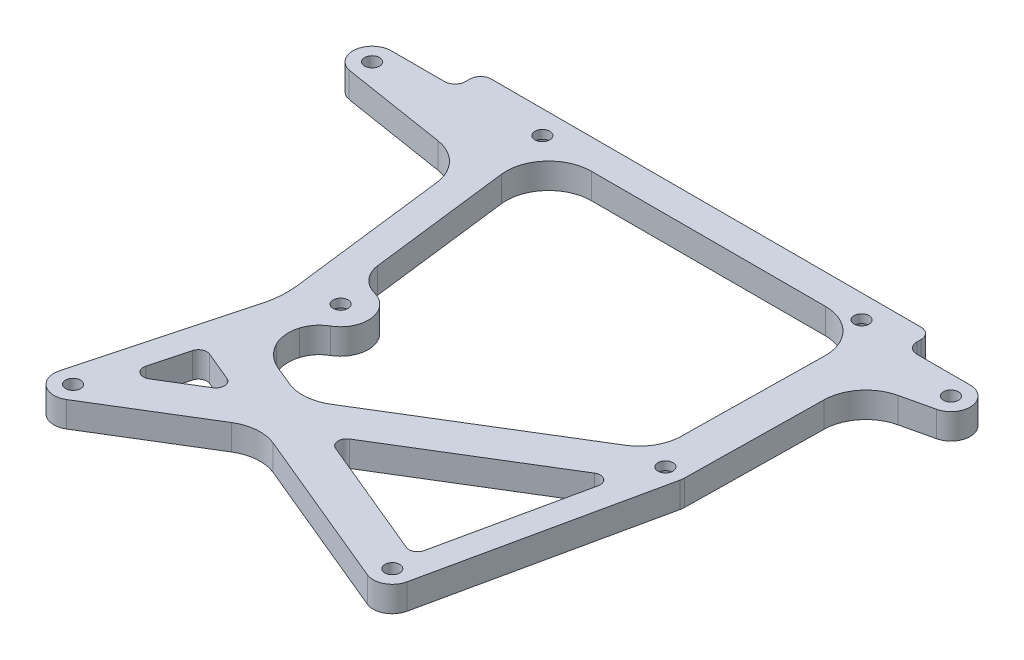
SolidWorks part; units mm, degrees
material "ABS"
ref_plane "Спереди" through (0, 0, 0) normal (0, 0, 1) x (1, 0, 0)
ref_plane "Сверху" through (0, 0, 0) normal (0, 1, 0) x (1, 0, 0)
ref_plane "Справа" through (0, 0, 0) normal (1, 0, 0) x (0, 0, -1)
sketch "Эскиз1" plane through (0, 0, 0) normal (0, 1, 0) x (1, 0, 0)
  line L0 (0, 100.75) -> (0, 0) construction
  line L1 (0, 0) -> (136, 0) construction
  line L2 (136, 0) -> (136, 100.75) construction
  line L3 (136, 100.75) -> (0, 100.75) construction
  line L4 (110, 105.75) -> (110, 52.79) construction
  line L5 (116.88, 52.79) -> (45.62, 52.79) construction
  line L6 (35, 105.75) -> (110, 105.75) construction
  line L7 (45.62, 47.74) -> (45.62, 52.79) construction
  line L9 (110, 105.75) -> (136, 100.75) construction
  line L10 (68, 100.75) -> (68, 0) construction
  line L11 (0, 105.25) -> (12.5, 105.25)
  line L12 (-1.0066, 96.364) -> (23.7971, 92.4355)
  line L13 (48, 104.25) -> (103, 104.25)
  line L14 (26.1533, 1.1647) -> (36.2211, 38.738)
  line L15 (112.8201, 41.0748) -> (105.5618, 7.4046)
  line L16 (47.628, 15.7413) -> (38.3168, 10.051)
  line L17 (121.2789, 51.8417) -> (109.8989, -0.9483)
  line L18 (32.1582, 83.7773) -> (36.7535, 46.3518)
  line L19 (15, 107.75) -> (15, 108.75)
  line L20 (112.9989, 94.1001) -> (112.5003, 60.8462)
  line L21 (121.8644, 85.0635) -> (121.3795, 52.7225)
  line L22 (51.2328, 27.4284) -> (55.7645, 25.5449)
  line L23 (40.3465, 22.2067) -> (47.3526, 19.2947)
  line L24 (107.7161, 52.4634) -> (64.8172, 26.2463)
  line L25 (109.8221, 43.2028) -> (74.0915, 21.3666)
  line L26 (35.342, 12.2751) -> (37.647, 20.8775)
  line L27 (74.3668, 17.8132) -> (102.8391, 5.9792)
  line L28 (65.9549, 11.563) -> (103.7729, -4.1554)
  line L29 (56.9023, 10.8616) -> (32.8466, -3.8397)
  line L30 (129.6138, 94.6573) -> (137.0123, 96.3653)
  line L31 (38.0745, 93.0313) -> (42.1383, 59.9344)
  line L32 (17.5, 111.25) -> (118.5, 111.25)
  line L33 (121, 108.75) -> (121, 107.75)
  line L34 (123.5, 105.25) -> (136, 105.25)
  circle A0 centre (35, 105.75) radius 1.75
  circle A1 centre (110, 105.75) radius 1.75
  circle A2 centre (116.88, 52.79) radius 1.75
  circle A3 centre (45.62, 47.74) radius 1.75
  circle A4 centre (0, 100.75) radius 1.75
  circle A5 centre (136, 100.75) radius 1.75
  circle A6 centre (30.5, 0) radius 1.75
  circle A7 centre (105.5, 0) radius 1.75
  arc A8 (121, 107.75) -> (123.5, 105.25) centre (123.5, 107.75) ccw
  arc A9 (118.5, 111.25) -> (121, 108.75) centre (118.5, 108.75) cw
  arc A10 (0, 105.25) -> (-1.0066, 96.364) centre (0, 100.75) ccw
  arc A11 (137.0123, 96.3653) -> (136, 105.25) centre (136, 100.75) ccw
  arc A12 (112.9989, 94.1001) -> (103, 104.25) centre (103, 94.25) ccw
  arc A13 (38.0745, 93.0313) -> (48, 104.25) centre (48, 94.25) cw
  arc A14 (15, 108.75) -> (17.5, 111.25) centre (17.5, 108.75) cw
  arc A15 (121.2789, 51.8417) -> (121.3795, 52.7225) centre (116.88, 52.79) ccw
  arc A16 (26.1533, 1.1647) -> (32.8466, -3.8397) centre (30.5, 0) ccw
  arc A17 (103.7729, -4.1554) -> (109.8989, -0.9483) centre (105.5, 0) ccw
  arc A18 (121.8644, 85.0635) -> (129.6138, 94.6573) centre (131.8633, 84.9136) cw
  arc A19 (32.1582, 83.7773) -> (23.7971, 92.4355) centre (22.2328, 82.5586) ccw
  arc A20 (65.9549, 11.563) -> (56.9023, 10.8616) centre (62.1169, 2.3289) ccw
  arc A21 (107.7161, 52.4634) -> (112.5003, 60.8462) centre (102.5014, 60.9961) ccw
  arc A22 (51.2328, 27.4284) -> (46.2025, 32.0417) centre (55.0708, 36.6626) cw
  arc A23 (64.8172, 26.2463) -> (55.7645, 25.5449) centre (59.6025, 34.779) cw
  arc A24 (36.7535, 46.3518) -> (36.2211, 38.738) centre (16.9026, 43.9144) cw
  arc A25 (105.5618, 7.4046) -> (102.8391, 5.9792) centre (103.6067, 7.826) cw
  arc A26 (112.8201, 41.0748) -> (109.8221, 43.2028) centre (110.865, 41.4963) ccw
  arc A27 (74.0915, 21.3666) -> (74.3668, 17.8132) centre (75.1344, 19.66) ccw
  arc A28 (47.3526, 19.2947) -> (47.628, 15.7413) centre (46.585, 17.4479) cw
  arc A29 (35.342, 12.2751) -> (38.3168, 10.051) centre (37.2739, 11.7575) ccw
  arc A30 (40.3465, 22.2067) -> (37.647, 20.8775) centre (39.5789, 20.3599) ccw
  arc A31 (15, 107.75) -> (12.5, 105.25) centre (12.5, 107.75) cw
  arc A32 (48.8562, 42.1029) -> (47.2889, 54.0221) centre (45.62, 47.74) ccw
  arc A33 (45.6501, 38.0883) -> (48.8562, 42.1029) centre (52.3413, 36.0321) cw
  arc A34 (42.1383, 59.9344) -> (47.2889, 54.0221) centre (49.0862, 60.7874) ccw
  arc A35 (46.2025, 32.0417) -> (45.6501, 38.0883) centre (53.2972, 35.7384) cw
  point P28 (121, 105.25)
  point P98 (111.1575, 54.79)
  dimension "D7" = 3.5
  dimension "D10" = 10
  dimension "D11" = 10
  dimension "D8" = 4.5
  dimension "D15" = 20
  dimension "D16" = 2
  dimension "D9" = 7
  dimension "D21" = 2.5
  dimension "D25" = 13
  dimension "D26" = 7
  dimension "D29" = 8
  dimension "D30" = 35
  dimension "D1" = 136
  dimension "D2" = 75
  dimension "D3" = 6.88
  dimension "D4" = 5.05
  dimension "D5" = 52.96
  dimension "D6" = 71.26
  dimension "D12" = 75
  dimension "D13" = 37.5
  dimension "D14" = 100.75
  dimension "D17" = 15
  dimension "D18" = 15
  dimension "D19" = 6
  dimension "D20" = 5
  dimension "D22" = 6
  dimension "D23" = 20
  dimension "D24" = 35
  dimension "D27" = 6
  dimension "D28" = 7
  dimension "D31" = 13
  dimension "D32" = 9
  dimension "D33" = 106
  dimension "D34" = 158
  dimension "D35" = 126
extrude "Бобышка-Вытянуть1" add sketch "Эскиз1" along normal blind 6
sketch "Эскиз2" plane through (0, 0, 0) normal (0, -1, 0) x (-1, 0, 0)
  circle A0 centre (-110, 105.75) radius 3
  circle A1 centre (-35, 105.75) radius 3
  circle A2 centre (-116.88, 52.79) radius 3
  circle A3 centre (-45.62, 47.74) radius 3
  dimension "D1" = 6
extrude "Вырез-Вытянуть1" cut sketch "Эскиз2" against normal blind 4
